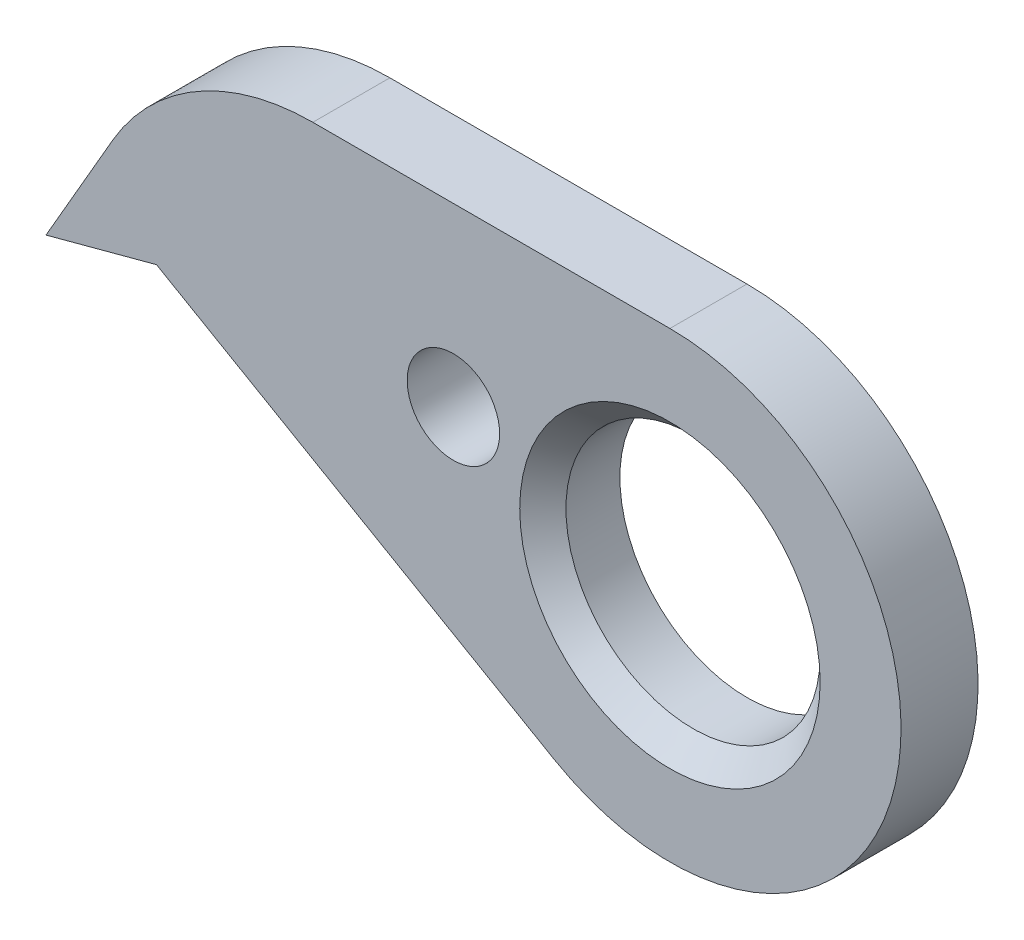
SolidWorks part; units mm, degrees
ref_plane "Front Plane" through (0, 0, 0) normal (0, 0, 1) x (1, 0, 0)
ref_plane "Top Plane" through (0, 0, 0) normal (0, 1, 0) x (1, 0, 0)
ref_plane "Right Plane" through (0, 0, 0) normal (1, 0, 0) x (0, 0, -1)
sketch "Sketch1" plane through (0, 0, 0) normal (0, 0, 1) x (1, 0, 0)
  line L0 (0, 3) -> (-4.6359, 3)
  line L1 (0, 0) -> (-8.1, 0) construction
  line L2 (-6.6657, 0.3843) -> (-1.5, -2.5981)
  line L3 (-8.1, 0) -> (-6.6657, 0.3843)
  line L4 (-8.1, 0) -> (-7.234, 1.5)
  arc A0 (-1.5, -2.5981) -> (0, 3) centre (0, 0) ccw
  arc A1 (-7.234, 1.5) -> (-4.6359, 3) centre (-4.6359, 0) cw
  dimension "D1" = 6
  dimension "D6" = 3
  dimension "D2" = 30
  dimension "D3" = 11.1
  dimension "D4" = 15
  dimension "D5" = 45
extrude "Boss-Extrude1" add sketch "Sketch1" against normal blind 1
sketch "Sketch2" plane through (0, 0, 0) normal (0, 0, 1) x (1, 0, 0)
  circle A0 centre (0, 0) radius 1.65
  dimension "D1" = 3.3
extrude "Cut-Extrude1" cut sketch "Sketch2" against normal up to next
chamfer "Chamfer1" distance 0.3 angle 45 1 edges at (1.65, 0, 0)
hole_wizard "Ø1.2 (1.2) Diameter Hole1" positions "Sketch4" profile "Sketch3" hole size "Ø1.2" standard "DIN" end condition through all
sketch "Sketch4" plane through (0, 0, 0) normal (0, 0, 1) x (1, 0, 0)
  line L0 (0, 0) -> (-2.8114, 0.7114) construction
  line L1 (-0.1516, 0.0384) -> (-2.9, 0) construction
  circle A0 centre (0, 0) radius 2.9 construction
  point P0 (-2.8114, 0.7114)
  dimension "D1" = 15
  dimension "D2" = 5.8
sketch "Sketch3" plane through (-2.8114, 0.7114, 0) normal (1, 0, 0) x (0, -1, 0)
  line L0 (0, 0) -> (0, 1)
  line L1 (0, 1) -> (0.6, 1)
  line L2 (0.6, 1) -> (0.6, 0)
  line L5 (0.6, 0) -> (0, 0)
  line L11 (0, -6.35) -> (0, 107.95) construction
  dimension "Thru Hole Dia." = 1.2
  dimension "Thru Hole Depth" = 1
